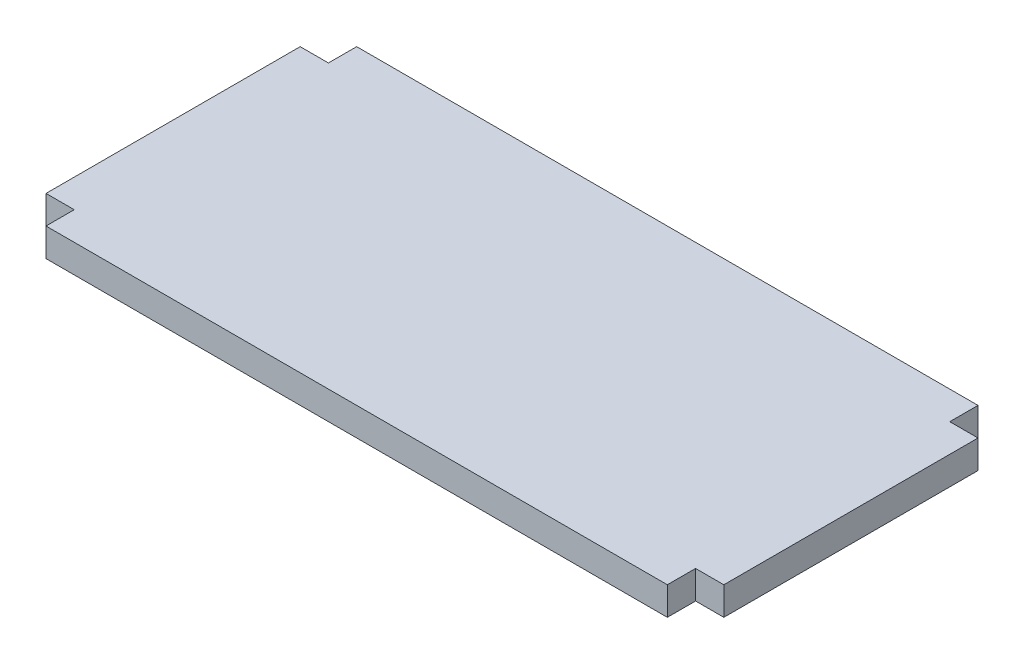
SolidWorks part; units mm, degrees
ref_plane "Alzado" through (0, 0, 0) normal (0, 0, 1) x (1, 0, 0)
ref_plane "Planta" through (0, 0, 0) normal (0, 1, 0) x (1, 0, 0)
ref_plane "Vista lateral" through (0, 0, 0) normal (1, 0, 0) x (0, 0, -1)
sketch "Croquis1" plane through (0, 0, 0) normal (0, 1, 0) x (1, 0, 0)
  line L0 (550, 275) -> (550, 225)
  line L1 (-600, 275) -> (600, 275)
  line L2 (-600, 275) -> (-600, -275)
  line L3 (-600, -275) -> (600, -275)
  line L4 (600, 275) -> (600, -275)
  line L5 (-600, 275) -> (600, -275) construction
  line L6 (-600, -275) -> (600, 275) construction
  line L7 (-600, 275) -> (-550, 275)
  line L8 (-600, 275) -> (-600, 225)
  line L9 (-600, 225) -> (-550, 225)
  line L10 (-550, 275) -> (-550, 225)
  line L11 (-600, 275) -> (-550, 225) construction
  line L12 (-600, 225) -> (-550, 275) construction
  line L13 (550, 275) -> (600, 275)
  line L14 (600, 275) -> (600, 225)
  line L15 (550, 225) -> (600, 225)
  line L16 (550, -225) -> (550, -275)
  line L17 (550, -225) -> (600, -225)
  line L18 (600, -225) -> (600, -275)
  line L19 (550, -275) -> (600, -275)
  line L20 (-600, -225) -> (-600, -275)
  line L21 (-600, -225) -> (-550, -225)
  line L22 (-550, -225) -> (-550, -275)
  line L23 (-600, -275) -> (-550, -275)
  point P0 (0, 0)
  point P6 (-575, 250)
  dimension "D1" = 50
  dimension "D2" = 50
  dimension "D3" = 1200
  dimension "D4" = 550
  dimension "D5" = 2
  dimension "D6" = 2
extrude "Saliente-Extruir1" add sketch "Croquis1" along normal blind 50 contours L21 L22 L3 L16 L17 L4 L15 L0 L1 L10 L9 L2
